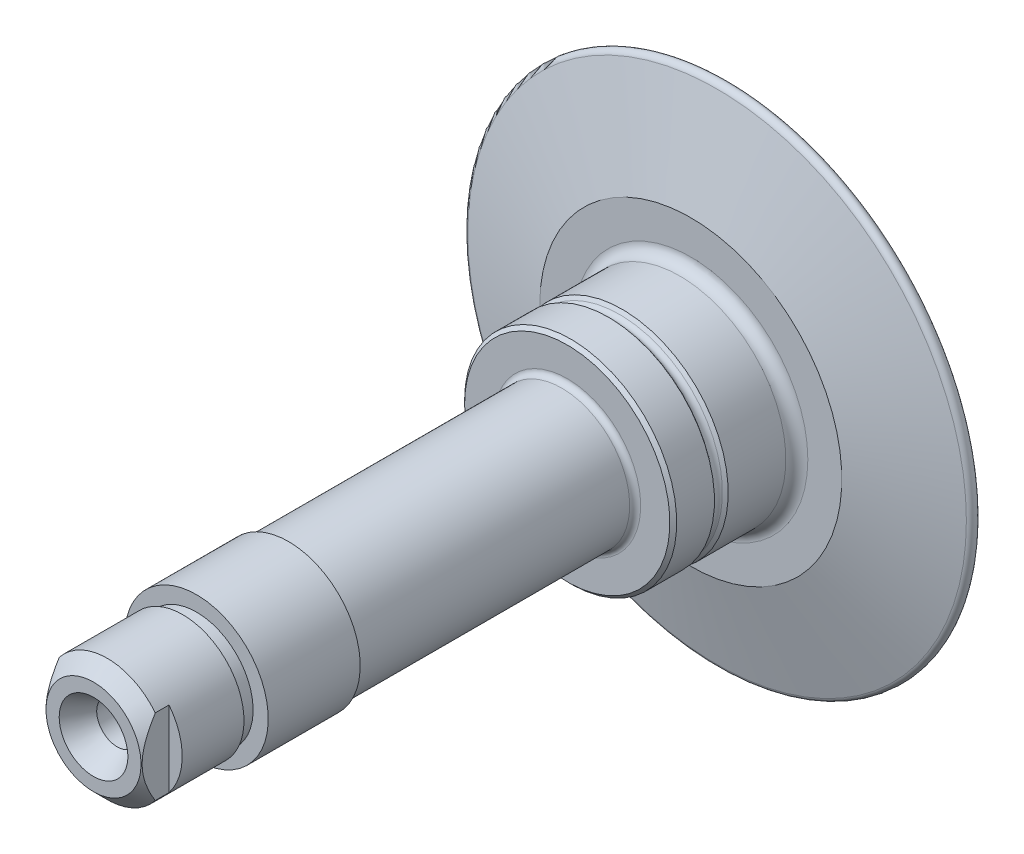
SolidWorks part; units mm, degrees
material "EN39B"
ref_plane "Front Plane" through (0, 0, 0) normal (0, 0, 1) x (1, 0, 0)
ref_plane "Top Plane" through (0, 0, 0) normal (0, 1, 0) x (1, 0, 0)
ref_plane "Right Plane" through (0, 0, 0) normal (1, 0, 0) x (0, 0, -1)
sketch "Sketch1" plane through (0, 0, 0) normal (1, 0, 0) x (0, 0, -1)
  line L0 (0, 0) -> (-65.6247, 0) construction
  line L1 (-14.25, 7.725) -> (-11.5, 7.725)
  line L2 (-5.5, 8.525) -> (-5.5, 11)
  line L3 (-5.5, 11) -> (-3.5829, 18.1546)
  line L4 (-14.25, 7.725) -> (-14.5, 7.475)
  line L5 (-14.5, 7.475) -> (-14.5, 5.35)
  line L6 (-14.9, 4.95) -> (-34.8, 4.95)
  line L7 (-34.8, 4.95) -> (-34.8, 5.225)
  line L8 (-34.8, 5.225) -> (-41.5, 5.225)
  line L9 (-41.5, 5.225) -> (-41.5, 4.125)
  line L10 (-42.5, 4.46) -> (-48, 4.46)
  line L11 (-48, 4.46) -> (-49, 3.46)
  line L12 (-49, 3.46) -> (-49, 2.5)
  line L13 (0, 0) -> (-43.2679, 0)
  line L14 (-42.5, 4.46) -> (-42.5, 4.125)
  line L15 (-42.5, 4.125) -> (-41.5, 4.125)
  line L16 (-49, 2.5) -> (-47.2679, 1.5)
  line L17 (-47.2679, 1.5) -> (-44.1692, 1.5)
  line L18 (-44.1692, 1.5) -> (-43.2679, 0)
  line L19 (-11, 9.6309) -> (-11, -0.9096) construction
  line L20 (-10.5, 7.725) -> (-6.3, 7.725)
  line L21 (-11.5, 7.725) -> (-11.3173, 7.487)
  line L22 (-10.5, 7.725) -> (-10.6827, 7.487)
  arc A0 (-2.8181, 18.1721) -> (0, 0) centre (-60, 0) cw
  arc A1 (-2.8181, 18.1721) -> (-3.5829, 18.1546) centre (-3.1979, 18.0514) ccw
  arc A2 (-6.3, 7.725) -> (-5.5, 8.525) centre (-6.3, 8.525) ccw
  arc A3 (-14.5, 5.35) -> (-14.9, 4.95) centre (-14.9, 5.35) cw
  arc A4 (-10.6827, 7.487) -> (-11.3173, 7.487) centre (-11, 7.7305) cw
  dimension "D12" = 49
  dimension "D13" = 75
  dimension "D14" = 36.9
  dimension "D15" = 60
  dimension "D17" = 0.8
  dimension "D18" = 0.4
  dimension "D28" = 0.4
  dimension "D29" = 75
  dimension "D1" = 15.45
  dimension "D2" = 22
  dimension "D3" = 0.25
  dimension "D4" = 45
  dimension "D5" = 9.9
  dimension "D6" = 10.45
  dimension "D7" = 8.92
  dimension "D8" = 7.5
  dimension "D9" = 36
  dimension "D10" = 6.7
  dimension "D11" = 9
  dimension "D16" = 1
  dimension "D19" = 1
  dimension "D20" = 8.25
  dimension "D21" = 3
  dimension "D22" = 59
  dimension "D23" = 4
  dimension "D24" = 5
  dimension "D25" = 30
  dimension "D26" = 3.5
  dimension "D27" = 1
revolve "Revolve1" add sketch "Sketch1" angle 360 about L0
cosmetic thread "Cosmetic Thread1" parameters "D2"=8.25
sketch "Sketch2" plane through (0, 0, 49) normal (0, 0, 1) x (1, 0, 0)
  line L0 (0, 8.525) -> (0, -10.7875) construction
  line L1 (0, 0) -> (13.5036, 0) construction
  line L2 (3.5, 6.1191) -> (9.1409, 6.1191)
  line L3 (3.5, 6.1191) -> (3.5, -6.1191)
  line L4 (3.5, -6.1191) -> (9.1409, -6.1191)
  line L5 (9.1409, 6.1191) -> (9.1409, -6.1191)
  line L6 (-3.5, 6.1191) -> (-9.1409, 6.1191)
  line L7 (-9.1409, 6.1191) -> (-9.1409, -6.1191)
  line L8 (-3.5, -6.1191) -> (-9.1409, -6.1191)
  line L9 (-3.5, 6.1191) -> (-3.5, -6.1191)
  circle A0 centre (0, 0) radius 8.525 construction
  circle A1 centre (0, 0) radius 11 construction
  dimension "D1" = 18.2818
  dimension "D2" = 7
extrude "Cut-Extrude1" cut sketch "Sketch2" against normal blind 2
